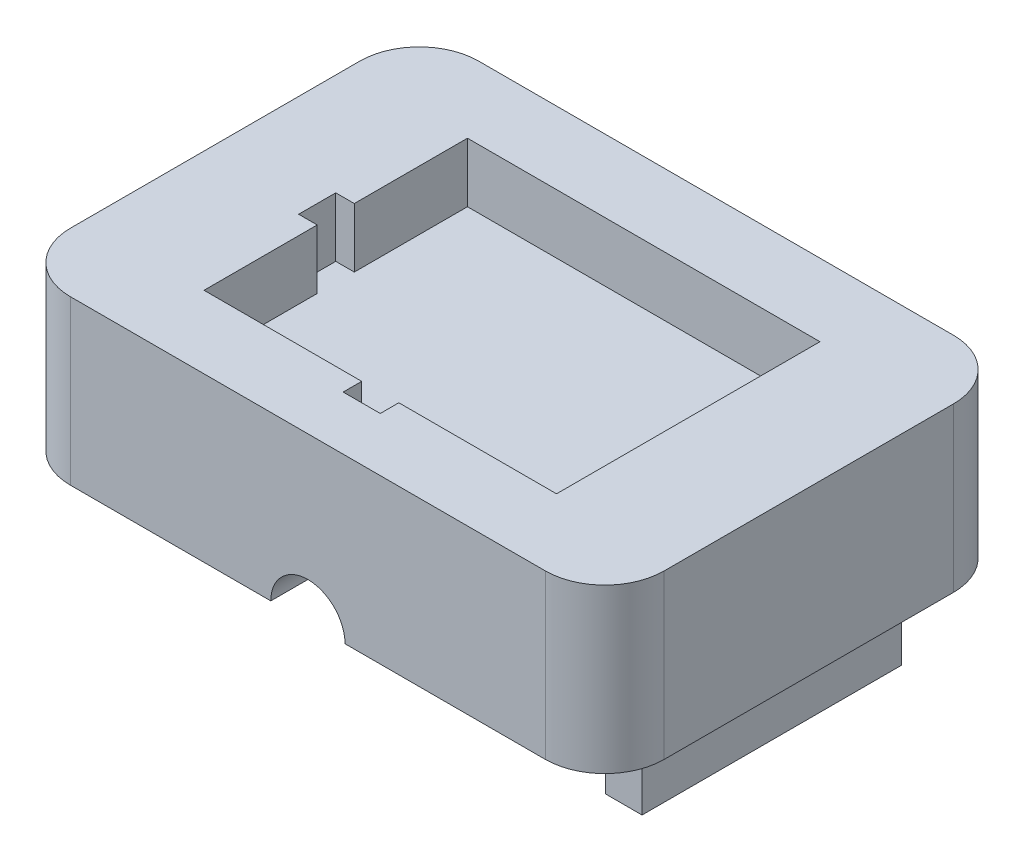
SolidWorks part; units mm, degrees
ref_plane "Alzado" through (0, 0, 0) normal (0, 0, 1) x (1, 0, 0)
ref_plane "Planta" through (0, 0, 0) normal (0, 1, 0) x (1, 0, 0)
ref_plane "Vista lateral" through (0, 0, 0) normal (1, 0, 0) x (0, 0, -1)
sketch "Croquis1" plane through (0, 0, 0) normal (0, 0, 1) x (1, 0, 0)
  line L0 (-5, 0) -> (-40, 0)
  line L1 (40, 0) -> (5, 0)
  line L2 (40, 0) -> (40, 22)
  line L3 (40, 22) -> (-40, 22)
  line L4 (-40, 0) -> (-40, 22)
  circle A0 centre (0, 0) radius 5
  dimension "D5" = 10
  dimension "D1" = 40
  dimension "D2" = 80
  dimension "D3" = 22
  dimension "D4" = 0
  dimension "D6" = 0
extrude "Saliente-Extruir1" add sketch "Croquis1" along normal blind 55 contours A0 L1 L2 L3 L4 L0
ref_plane "Plano1" through (0, 0, 27.5) normal (0, 0, 1) x (1, 0, 0)
sketch "Croquis2" plane through (0, 0, 27.5) normal (0, 0, 1) x (1, 0, 0)
  circle A0 centre (0, 0) radius 9.525
  dimension "D1" = 19.05
extrude "Cortar-Extruir1" cut sketch "Croquis2" against normal mid plane 6.05
sketch "Croquis3" plane through (0, 0, 0) normal (0, -1, 0) x (1, 0, 0)
  line L0 (0, 58.6648) -> (0, -5.1304) construction
  line L1 (-35, 44.975) -> (-30.05, 44.975)
  line L2 (-35, 44.975) -> (-35, 10.025)
  line L3 (-35, 10.025) -> (-30.05, 10.025)
  line L4 (-30.05, 44.975) -> (-30.05, 10.025)
  line L5 (-40, 55) -> (-40, 0) construction
  line L6 (-5, 55) -> (-40, 55) construction
  line L11 (40, 55) -> (5, 55) construction
  line L12 (30.05, 10.025) -> (35, 10.025)
  line L13 (30.05, 10.025) -> (30.05, 44.975)
  line L14 (30.05, 44.975) -> (35, 44.975)
  line L15 (35, 10.025) -> (35, 44.975)
  line L16 (30.05, 10.025) -> (35, 44.975) construction
  line L17 (30.05, 44.975) -> (35, 10.025) construction
  line L18 (40, 55) -> (40, 0) construction
  point P9 (-30.05, 27.5)
  point P12 (32.525, 27.5)
  dimension "D1" = 4.95
  dimension "D2" = 5
  dimension "D3" = 34.95
  dimension "D4" = 27.5
  dimension "D5" = 34.95
  dimension "D6" = 27.5
  dimension "D7" = 4.95
  dimension "D8" = 5
extrude "Saliente-Extruir2" add sketch "Croquis3" along normal blind 10
sketch "Croquis6" plane through (0, 22, 0) normal (0, 1, 0) x (1, 0, 0)
  line L18 (-40, -27.5) -> (-26.25, -27.5) construction
  line L19 (-40, -55) -> (-40, 0) construction
  line L21 (-23.75, -45.25) -> (-2.5, -45.25)
  line L22 (-23.75, -45.25) -> (-23.75, -30)
  line L23 (-23.75, -9.75) -> (23.75, -9.75)
  line L24 (23.75, -45.25) -> (23.75, -9.75)
  line L25 (-23.75, -25) -> (-23.75, -9.75)
  line L26 (2.5, -45.25) -> (23.75, -45.25)
  line L27 (-23.75, -25) -> (-26.25, -25)
  line L28 (-26.25, -25) -> (-26.25, -30)
  line L29 (-26.25, -30) -> (-23.75, -30)
  line L32 (-2.5, -45.25) -> (-2.5, -47.75)
  line L33 (-2.5, -47.75) -> (2.5, -47.75)
  line L34 (2.5, -47.75) -> (2.5, -45.25)
  line L36 (0, -27.5) -> (53.1647, -27.5) construction
  point P4 (0, -27.5)
  dimension "D1" = 47.5
  dimension "D2" = 35.5
  dimension "D3" = 15.25
  dimension "D4" = 21.25
  dimension "D5" = 2.5
  dimension "D8" = 2.5
fillet "Redondeo1" radius 8 4 edges at (40, 11, 0) (40, 11, 55) (-40, 11, 55) (-40, 11, 0)
extrude "Cortar-Extruir2" cut sketch "Croquis6" against normal blind 8
